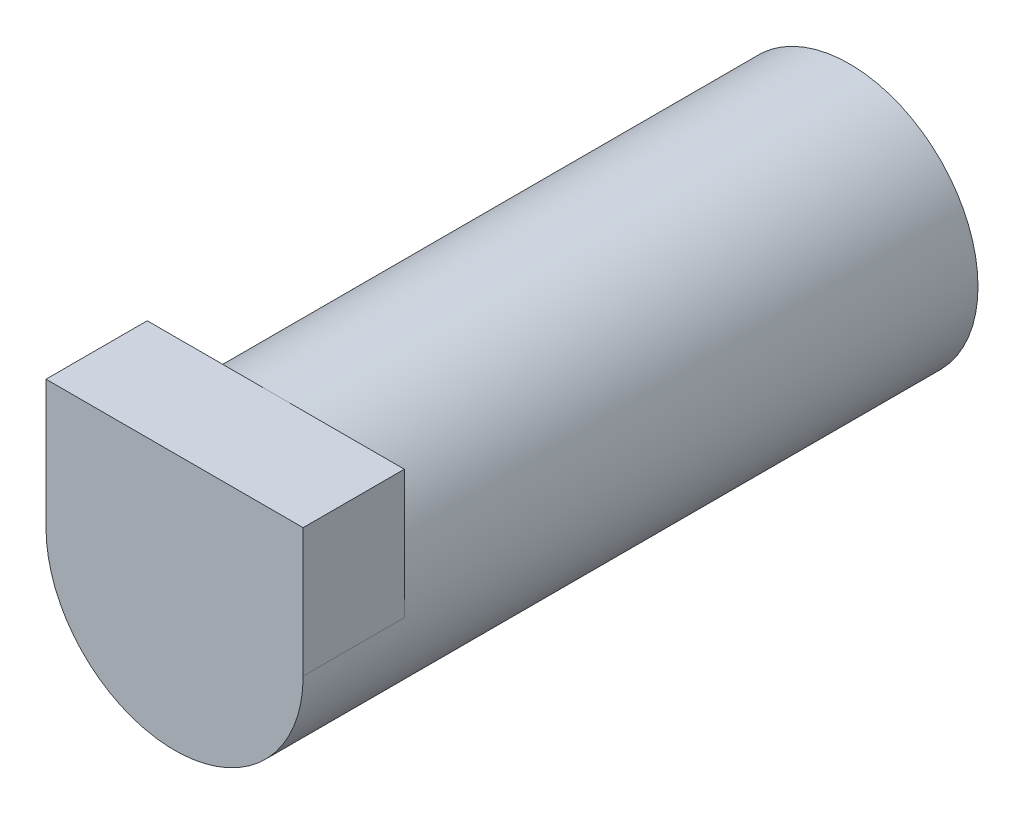
SolidWorks part; units mm, degrees
ref_plane "Alzado" through (0, 0, 0) normal (0, 0, 1) x (1, 0, 0)
ref_plane "Planta" through (0, 0, 0) normal (0, 1, 0) x (1, 0, 0)
ref_plane "Vista lateral" through (0, 0, 0) normal (1, 0, 0) x (0, 0, -1)
sketch "Croquis1" plane through (0, 0, 0) normal (0, 0, 1) x (1, 0, 0)
  circle A0 centre (0, 0) radius 19.05
  dimension "D1" = 38.1
extrude "Saliente-Extruir1" add sketch "Croquis1" along normal blind 100
sketch "Croquis2" plane through (0, 0, 100) normal (0, 0, 1) x (1, 0, 0)
  line L0 (0, 19.05) -> (-19.05, 19.05)
  line L1 (-19.05, 0) -> (-19.05, 19.05)
  line L2 (0, 19.05) -> (19.05, 19.05)
  line L3 (19.05, 0) -> (19.05, 19.05)
  circle A0 centre (0, 0) radius 19.05 construction
  arc A1 (19.05, 0) -> (-19.05, 0) centre (0, 0) ccw
  circle M1 centre (0, 0) radius 19.05
extrude "Saliente-Extruir2" add sketch "Croquis2" against normal blind 15 contours L3 L2 M1 | L1 L0 M1
